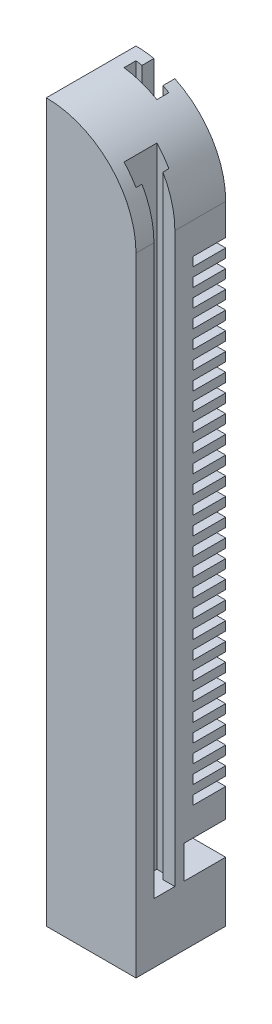
SolidWorks part; units mm, degrees
material "Alumina"
ref_plane "Front Plane" through (0, 0, 0) normal (0, 0, 1) x (1, 0, 0)
ref_plane "Top Plane" through (0, 0, 0) normal (0, 1, 0) x (1, 0, 0)
ref_plane "Right Plane" through (0, 0, 0) normal (1, 0, 0) x (0, 0, -1)
sketch "Sketch1" plane through (0, 0, 0) normal (0, 1, 0) x (1, 0, 0)
  line L1 (0, 0) -> (15, 0)
  line L2 (0, 0) -> (0, 15)
  line L3 (0, 15) -> (15, 15)
  line L4 (15, 0) -> (15, 15)
  dimension "D1" = 15
  dimension "D2" = 15
extrude "Boss-Extrude1" add sketch "Sketch1" along normal blind 120
sketch "Sketch3" plane through (0, 120, 0) normal (0, 1, 0) x (1, 0, 0)
  line L0 (15, 3) -> (13, 3)
  line L1 (15, 0) -> (15, 15) construction
  line L2 (13, 3) -> (13, 2)
  line L3 (13, 2) -> (11, 2)
  line L4 (11, 2) -> (11, 7.5)
  line L5 (11, 7.5) -> (13, 7.5)
  line L6 (13, 7.5) -> (13, 6.5)
  line L7 (13, 6.5) -> (15, 6.5)
  line L8 (15, 6.5) -> (15, 3)
  line L9 (15, 15) -> (0, 0) construction
  line L10 (3, 13) -> (2, 13)
  line L11 (6.5, 15) -> (3, 15)
  line L12 (7.5, 13) -> (6.5, 13)
  line L13 (6.5, 13) -> (6.5, 15)
  line L14 (7.5, 11) -> (7.5, 13)
  line L15 (2, 11) -> (7.5, 11)
  line L16 (2, 13) -> (2, 11)
  line L17 (3, 15) -> (3, 13)
  dimension "D1" = 3
  dimension "D2" = 5.5
  dimension "D3" = 3.5
  dimension "D4" = 1
  dimension "D5" = 2
  dimension "D6" = 2
extrude "Cut-Extrude1" cut sketch "Sketch3" against normal blind 110
sketch "Sketch5" plane through (0, 120, 0) normal (0, 1, 0) x (1, 0, 0)
  line L0 (15, 15) -> (15, 9.5)
  line L2 (15, 9.5) -> (9.5, 15)
  line L4 (9.5, 15) -> (15, 15)
  dimension "D1" = 5.5
  dimension "D2" = 5.5
extrude "Cut-Extrude2" cut sketch "Sketch5" against normal blind 1.5 from offset 20.25 offset against normal yes
pattern_linear "LPattern1" count 27 spacing 3 along (0, -1, 0) of "Cut-Extrude2"
sketch "Sketch6" plane through (0, 0, 0) normal (0, -1, 0) x (1, 0, 0)
  line L5 (15, -15) -> (8, -15)
  line L9 (15, -8) -> (15, -15)
  line L10 (8, -15) -> (8, -8)
  line L11 (8, -8) -> (15, -8)
  dimension "D1" = 7
  dimension "D2" = 7
extrude "Cut-Extrude3" cut sketch "Sketch6" against normal blind 5.5 from offset 10 offset against normal yes
sketch "Sketch12" plane through (0, 0, 0) normal (0, 0, 1) x (1, 0, 0)
  line L0 (0, 120) -> (0, 110) construction
  line L1 (0, 120) -> (0, 0) construction
  line L2 (15, 120) -> (15, 0) construction
  line L3 (0, 120) -> (15, 120) construction
  line L4 (0, 120) -> (15, 120)
  line L5 (15, 120) -> (15, 105)
  arc A0 (15, 105) -> (0, 120) centre (0, 105) ccw
  dimension "D1" = 10
extrude "Cut-Extrude4" cut sketch "Sketch12" against normal through all
